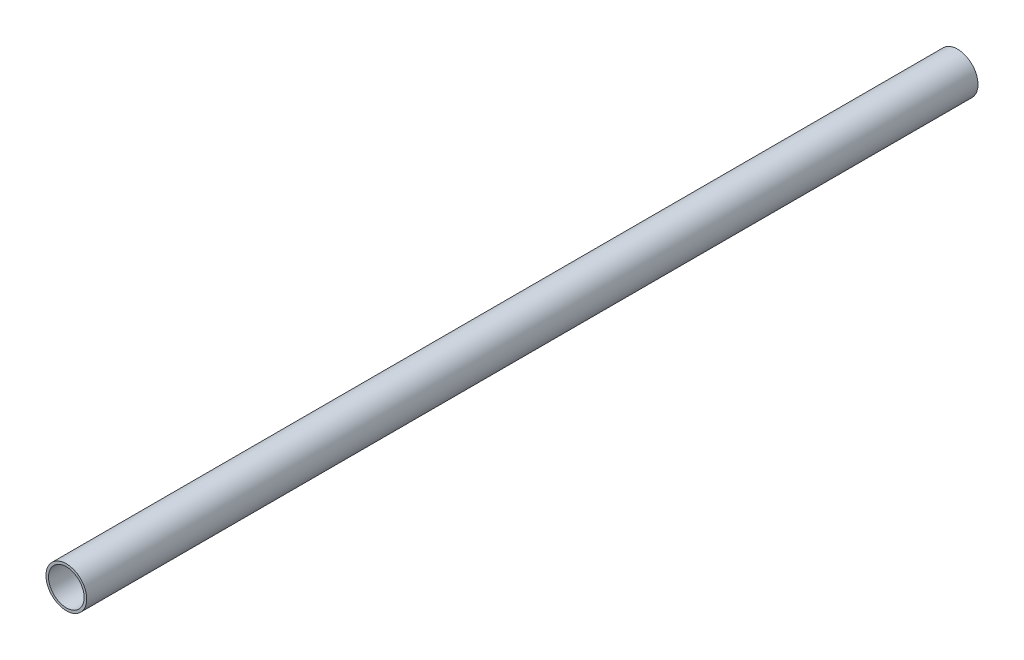
SolidWorks part; units mm, degrees
ref_plane "Front Plane" through (0, 0, 0) normal (0, 0, 1) x (1, 0, 0)
ref_plane "Top Plane" through (0, 0, 0) normal (0, 1, 0) x (1, 0, 0)
ref_plane "Right Plane" through (0, 0, 0) normal (1, 0, 0) x (0, 0, -1)
sketch "Sketch1" plane through (0, 0, 0) normal (0, 0, 1) x (1, 0, 0)
  circle A0 centre (0, 0) radius 16
  circle A1 centre (0, 0) radius 14
  point P3 (0, 0)
  dimension "D1" = 32
  dimension "D2" = 2
extrude "Boss-Extrude1" add sketch "Sketch1" along normal blind 700
